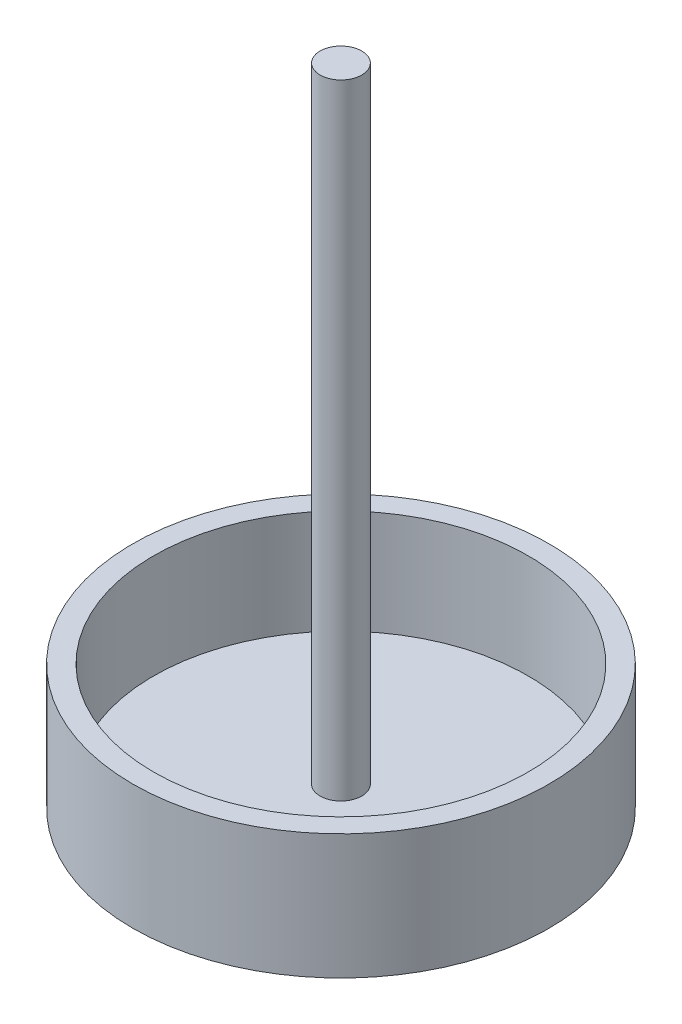
SolidWorks part; units mm, degrees
ref_plane "Front Plane" through (0, 0, 0) normal (0, 0, 1) x (1, 0, 0)
ref_plane "Top Plane" through (0, 0, 0) normal (0, 1, 0) x (1, 0, 0)
ref_plane "Right Plane" through (0, 0, 0) normal (1, 0, 0) x (0, 0, -1)
sketch "Sketch1" plane through (0, 0, 0) normal (0, 1, 0) x (1, 0, 0)
  circle A0 centre (0, 0) radius 5
extrude "Boss-Extrude1" add sketch "Sketch1" along normal blind 3
sketch "Sketch2" plane through (0, 3, 0) normal (0, 1, 0) x (1, 0, 0)
  circle A0 centre (0, 0) radius 4.5
extrude "Cut-Extrude1" cut sketch "Sketch2" against normal blind 2.5
sketch "Sketch3" plane through (0, 0.5, 0) normal (0, 1, 0) x (1, 0, 0)
  circle A0 centre (0, 0) radius 0.5
extrude "Boss-Extrude2" add sketch "Sketch3" along normal blind 15
